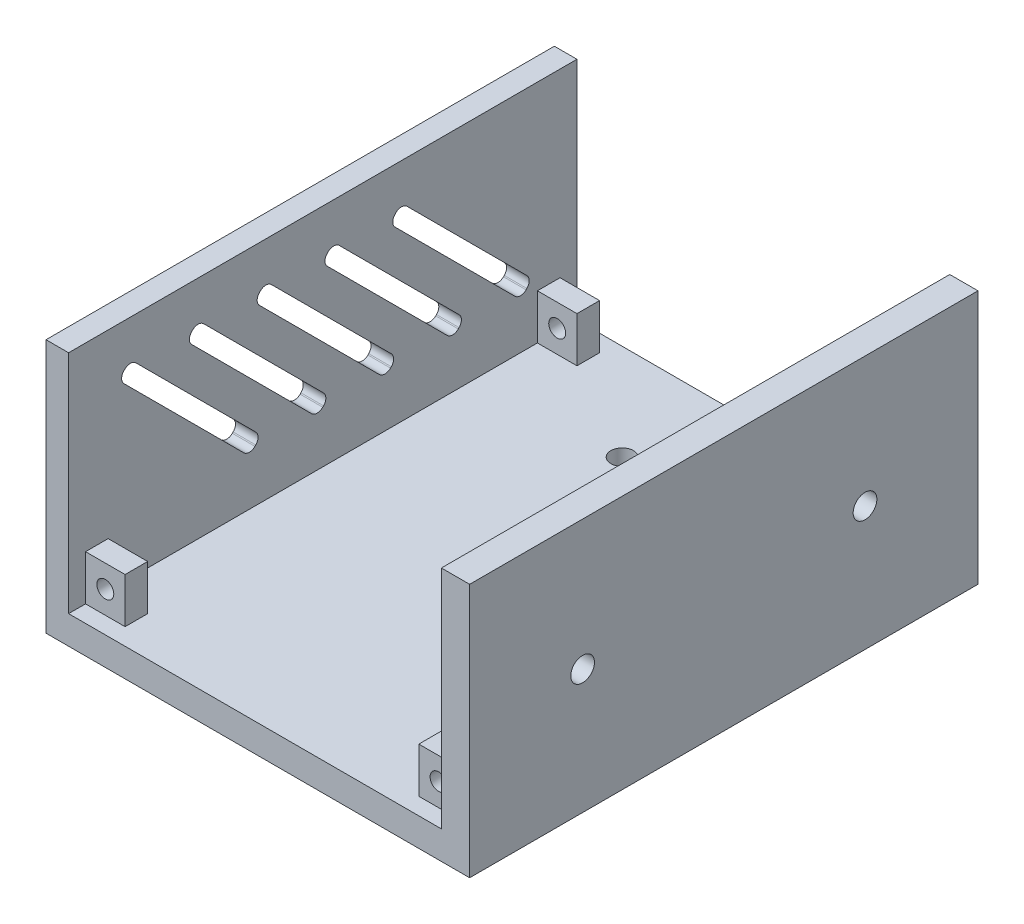
SolidWorks part; units mm, degrees
ref_plane "Front Plane" through (0, 0, 0) normal (0, 0, 1) x (1, 0, 0)
ref_plane "Top Plane" through (0, 0, 0) normal (0, 1, 0) x (1, 0, 0)
ref_plane "Right Plane" through (0, 0, 0) normal (1, 0, 0) x (0, 0, -1)
sketch "Sketch1" plane through (0, 0, 0) normal (0, 0, 1) x (1, 0, 0)
  line L1 (-37.5, -2.5) -> (37.5, -2.5)
  line L2 (-37.5, -2.5) -> (-37.5, 2.5)
  line L3 (-37.5, 2.5) -> (37.5, 2.5)
  line L4 (37.5, -2.5) -> (37.5, 2.5)
  line L5 (-37.5, -2.5) -> (37.5, 2.5) construction
  line L6 (-37.5, 2.5) -> (37.5, -2.5) construction
  line L7 (37.5, 2.5) -> (32.5, 2.5)
  line L8 (37.5, 2.5) -> (37.5, 42.5)
  line L9 (37.5, 42.5) -> (32.5, 42.5)
  line L10 (32.5, 2.5) -> (32.5, 42.5)
  point P0 (0, 0)
  dimension "D1" = 5
  dimension "D2" = 5
  dimension "D3" = 75
  dimension "D4" = 45
extrude "Boss-Extrude1" add sketch "Sketch1" along normal blind 90 contours L1 L4 L3 L2 | L10 L3 L8 L9
sketch "Sketch2" plane through (32.5, 0, 0) normal (-1, 0, 0) x (0, 0, 1)
  line L0 (0, 2.5) -> (0, 42.5) construction
  line L2 (90, 42.5) -> (0, 42.5) construction
  circle A0 centre (20, 19.5) radius 2.1
  circle A1 centre (70, 19.5) radius 2.1
  dimension "D1" = 4.2
  dimension "D2" = 4.2
  dimension "D3" = 20
  dimension "D4" = 50
  dimension "D5" = 23
extrude "Cut-Extrude1" cut sketch "Sketch2" against normal through all
sketch "Sketch4" plane through (0, 2.5, 0) normal (0, 1, 0) x (1, 0, 0)
  line L0 (-37.5, 0) -> (32.5, 0) construction
  line L1 (-37.5, -90) -> (-33.5, -90)
  line L2 (-37.5, -90) -> (-37.5, 0)
  line L3 (-37.5, 0) -> (-33.5, 0)
  line L4 (-33.5, -90) -> (-33.5, 0)
  dimension "D1" = 4
extrude "Boss-Extrude2" add sketch "Sketch4" along normal up to surface (40 mm away) up to face at (35, 42.5, 45)
sketch "Sketch6" plane through (0, 2.5, 0) normal (0, 1, 0) x (1, 0, 0)
  line L0 (-33.5, -90) -> (-33.5, 0) construction
  line L1 (-33.5, -3) -> (-26.5, -3)
  line L2 (-33.5, -3) -> (-33.5, -7)
  line L3 (-33.5, -7) -> (-26.5, -7)
  line L4 (-26.5, -3) -> (-26.5, -7)
  line L5 (-33.5, 0) -> (32.5, 0) construction
  line L6 (-33.5, -45) -> (32.5, -45) construction
  line L7 (32.5, -90) -> (32.5, 0) construction
  line L8 (-0.5, 0) -> (-0.5, -90) construction
  line L9 (-33.5, -90) -> (32.5, -90) construction
  line L10 (25.5, -3) -> (25.5, -7)
  line L11 (32.5, -7) -> (25.5, -7)
  line L12 (32.5, -3) -> (32.5, -7)
  line L13 (32.5, -3) -> (25.5, -3)
  line L14 (32.5, -87) -> (25.5, -87)
  line L15 (32.5, -87) -> (32.5, -83)
  line L16 (32.5, -83) -> (25.5, -83)
  line L17 (25.5, -87) -> (25.5, -83)
  line L18 (-26.5, -87) -> (-26.5, -83)
  line L19 (-33.5, -83) -> (-26.5, -83)
  line L20 (-33.5, -87) -> (-33.5, -83)
  line L21 (-33.5, -87) -> (-26.5, -87)
  dimension "D1" = 3
  dimension "D2" = 4
  dimension "D3" = 7
extrude "Boss-Extrude4" add sketch "Sketch6" along normal blind 8
sketch "Sketch7" plane through (0, 2.5, 0) normal (0, 1, 0) x (1, 0, 0)
  line L0 (-33.5, -90) -> (32.5, -90) construction
  line L1 (32.5, -90) -> (32.5, 0) construction
  circle A0 centre (24.5, -68) radius 1.6
  circle A1 centre (-8.5, -17) radius 1.6
  dimension "D1" = 3.2
  dimension "D4" = 3.2
  dimension "D2" = 51
  dimension "D3" = 33
  dimension "D5" = 22
  dimension "D6" = 8
extrude "Cut-Extrude3" cut sketch "Sketch7" against normal through all
sketch "Sketch8" plane through (-37.5, 0, 0) normal (-1, 0, 0) x (0, 0, 1)
  line L0 (90, -2.5) -> (0, -2.5) construction
  line L1 (32.0613, 34.9899) -> (32.2027, 34.8485)
  line L2 (30.0814, 34.9899) -> (8.8686, 13.7772)
  line L3 (8.8686, 11.7973) -> (9.0101, 11.6559)
  line L4 (32.2027, 32.8686) -> (10.9899, 11.6559)
  line L5 (90, 42.5) -> (0, 42.5) construction
  line L6 (0, -2.5) -> (0, 42.5) construction
  arc A0 (8.8686, 13.7772) -> (8.8686, 11.7973) centre (9.8586, 12.7873) ccw
  arc A1 (9.0101, 11.6559) -> (10.9899, 11.6559) centre (10, 12.6458) ccw
  arc A2 (32.2027, 34.8485) -> (32.2027, 32.8686) centre (31.2127, 33.8586) cw
  arc A3 (32.0613, 34.9899) -> (30.0814, 34.9899) centre (31.0713, 34) ccw
  point P6 (9.3006, 3.6301)
  point P7 (26.8916, 27.8824)
  point P14 (33.1926, 33.8586)
  point P17 (31.0713, 35.9799)
  dimension "D3" = 1.4
  dimension "D1" = 45
  dimension "D2" = 3
  dimension "D4" = 30
  dimension "D5" = 8.5
  dimension "D6" = 10
extrude "Cut-Extrude4" cut sketch "Sketch8" against normal up to next
pattern_linear "LPattern1" count 5 spacing 12 along (0, 0, 1) of "Cut-Extrude4"
sketch "Sketch9" plane through (0, 0, 87) normal (0, 0, 1) x (1, 0, 0)
  line L0 (-26.5, 10.5) -> (-26.5, 2.5) construction
  line L1 (-33.5, 10.5) -> (-26.5, 10.5) construction
  line L3 (25.5, 10.5) -> (25.5, 2.5) construction
  circle A0 centre (-30, 6.5) radius 1.5
  circle A1 centre (29, 6.5) radius 1.5
  point P4 (0, 0)
  dimension "D1" = 3
  dimension "D2" = 3
  dimension "D5" = 3.5
  dimension "D3" = 3.5
  dimension "D4" = 4
extrude "Cut-Extrude5" cut sketch "Sketch9" against normal through all
hole_wizard "CSK for M4 Countersunk Flat Head Screw1" positions "3DSketch1" profile "Sketch10" countersink size "M4" standard "ISO" end condition through all
sketch3d "3DSketch1"
  line L0 (24.5, -2.5, 68) -> (24.5, 2.5, 68) construction
  line L1 (-8.5, -2.5, 17) -> (-8.5, 2.5, 17) construction
  point P0 (24.5, -2.5, 68)
  point P4 (-8.5, -2.5, 17)
sketch "Sketch10" plane through (24.5, -2.5, 68) normal (1, 0, 0) x (0, 0, -1)
  line L0 (0, 0) -> (0, 45)
  line L1 (0, 45) -> (2, 45)
  line L2 (2, 45) -> (2, 1.75)
  line L3 (2, 1.75) -> (3.75, 0)
  line L5 (3.75, 0) -> (0, 0)
  line L6 (-2, 1.75) -> (-3.75, 0) construction
  line L11 (0, -6.35) -> (0, 107.95) construction
  dimension "Thru Hole Dia." = 4
  dimension "Thru Hole Depth" = 45
  dimension "Near C'Sink Dia." = 7.5
  dimension "Near C'Sink Angle" = 90
